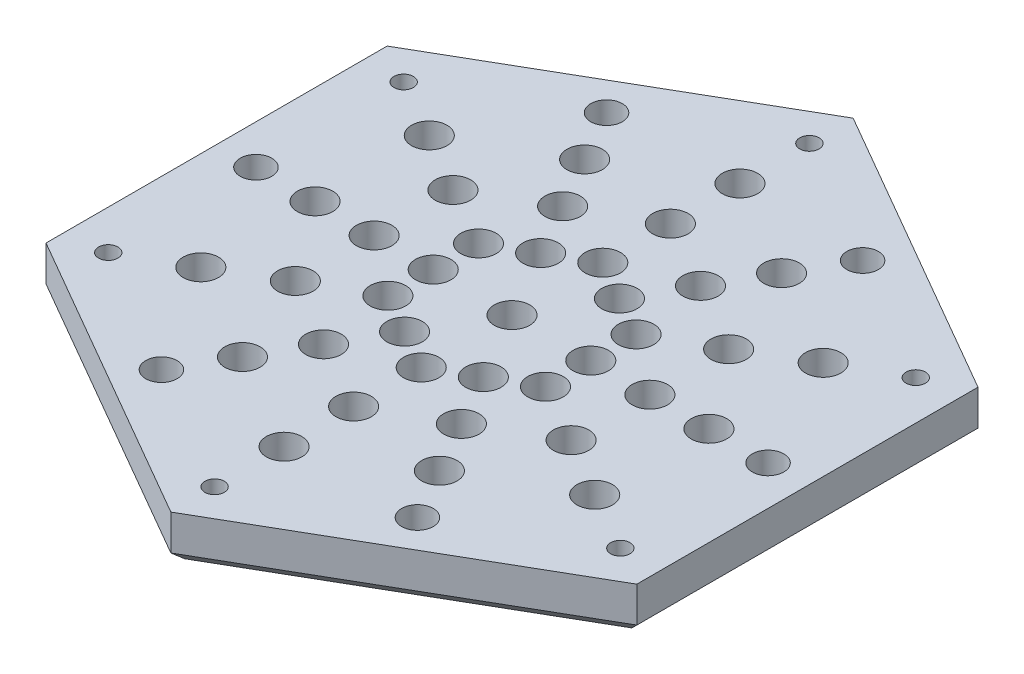
SolidWorks part; units mm, degrees
ref_plane "前基準面" through (0, 0, 0) normal (0, 0, 1) x (1, 0, 0)
ref_plane "上基準面" through (0, 0, 0) normal (0, 1, 0) x (1, 0, 0)
ref_plane "右基準面" through (0, 0, 0) normal (1, 0, 0) x (0, 0, -1)
ref_plane "平面1"
sketch "草圖1" plane through (0, 0, 0) normal (0, 1, 0) x (-1, 0, 0)
  line L0 (0, -86.6025) -> (-75, -43.3013)
  line L1 (-75, -43.3013) -> (-75, 43.3013)
  line L2 (-75, 43.3013) -> (0, 86.6025)
  line L3 (0, 86.6025) -> (75, 43.3013)
  line L4 (75, 43.3013) -> (75, -43.3013)
  line L5 (75, -43.3013) -> (0, -86.6025)
  dimension "D1" = 150
extrude "擠出1" add sketch "草圖1" along normal blind 12
chamfer "倒角1" distance 3 distance2 3 6 edges at (37.5, 0, 64.9519) (75, 0, 0) (-37.5, 0, 64.9519) (-75, 0, 0) (-37.5, 0, -64.9519) (37.5, 0, -64.9519)
sketch "草圖2" plane through (0, 12, 0) normal (0, 1, 0) x (-1, 0, 0)
  circle A0 centre (32.5, -56.5) radius 4
  circle A1 centre (-32.5, -56.5) radius 4
  circle A2 centre (65, 0) radius 4
  circle A3 centre (32.5, 56.5) radius 4
  circle A4 centre (-32.5, 56.5) radius 4
  circle A5 centre (-65, 0) radius 4
  dimension "D5" = 8
  dimension "D6" = 8
  dimension "D7" = 8
  dimension "D8" = 8
  dimension "D9" = 8
  dimension "D10" = 8
  dimension "D1" = 65
  dimension "D2" = 113
  dimension "D3" = 65
  dimension "D4" = 65
extrude "擠出2" cut sketch "草圖2" against normal blind 12 contours A4 | A3 | A5 | A1 | A0 | A2
hole_wizard "孔1" positions "草圖4" profile "草圖3" legacy
sketch "草圖4" plane through (0, 12, 0) normal (0, 1, 0) x (1, 0, 0)
  point P1 (0, 75.5)
  point P2 (-65, 37.5)
  point P3 (65, 37.5)
  point P4 (-65, -37.5)
  point P5 (65, -37.5)
  point P6 (0, -75.5)
sketch "草圖3" plane through (0, 12, -75.5) normal (1, 0, 0) x (0, 0, 1)
  line L0 (0, 0) -> (0, 18.5772)
  line L1 (0, 18.5772) -> (2.4585, 17.1)
  line L2 (2.4585, 17.1) -> (2.4585, 0)
  line L4 (2.4585, 0) -> (0, 0)
  line L6 (0, 18.5772) -> (-2.4585, 17.1) construction
  line L7 (0, -4.2442) -> (0, 117.3081) construction
  dimension "直徑" = 4.917
  dimension "深度" = 17.1
  dimension "導頭角度" = 118
cosmetic thread "裝飾螺紋線1" parameters "D1"=12, "D2"=6.294
cosmetic thread "裝飾螺紋線2" parameters "D1"=12, "D2"=6.294
cosmetic thread "裝飾螺紋線3" parameters "D1"=12, "D2"=6.294
cosmetic thread "裝飾螺紋線4" parameters "D1"=12, "D2"=6.294
cosmetic thread "裝飾螺紋線5" parameters "D1"=12, "D2"=6.294
cosmetic thread "裝飾螺紋線6" parameters "D1"=12, "D2"=6.294
sketch "草圖5" plane through (0, 12, 0) normal (0, 1, 0) x (-1, 0, 0)
  circle A0 centre (0, 0) radius 4.5
  dimension "D1" = 9
extrude "擠出4" cut sketch "草圖5" against normal blind 12
ref_plane "平面2" through (0, 12, 0) normal (0, 1, 0) x (1, 0, 0)
sketch "草圖6" plane through (0, 12, 0) normal (0, 1, 0) x (1, 0, 0)
  circle A0 centre (20, 0) radius 4.5
  circle A1 centre (35, 0) radius 4.5
  circle A2 centre (50, 0) radius 4.5
  dimension "D1" = 9
  dimension "D2" = 9
  dimension "D3" = 9
  dimension "D4" = 20
  dimension "D5" = 15
  dimension "D6" = 15
extrude "擠出3" cut sketch "草圖6" against normal blind 12 contours A0 | A1 | A2
ref_plane "平面3" through (0, 0, 0) normal (1, 0, 0) x (0, 1, 0)
mirror "鏡射5" about plane through (0, 0, 0) normal (1, 0, 0) of "擠出3"
ref_plane "平面4" through (0, 12, 0) normal (0, 1, 0) x (1, 0, 0)
sketch "草圖7" plane through (0, 12, 0) normal (0, 1, 0) x (1, 0, 0)
  circle A0 centre (20, 11.5) radius 4.5
  circle A1 centre (35, 20) radius 4.5
  circle A2 centre (50, 29) radius 4.5
  dimension "D1" = 9
  dimension "D2" = 9
  dimension "D3" = 9
extrude "擠出5" cut sketch "草圖7" against normal blind 12 contours A0 | A1 | A2
ref_plane "平面5" through (0, 0, 0) normal (0, 0, 1) x (1, 0, 0)
mirror "鏡射1" about plane through (0, 0, 0) normal (0, 0, 1) of "擠出5"
ref_plane "平面6" through (0, 0, 0) normal (1, 0, 0) x (0, 1, 0)
mirror "鏡射2" about plane through (0, 0, 0) normal (1, 0, 0) of "鏡射1", "擠出5"
ref_plane "平面7" through (0, 12, 0) normal (0, 1, 0) x (1, 0, 0)
sketch "草圖8" plane through (0, 12, 0) normal (0, 1, 0) x (1, 0, 0)
  circle A0 centre (0, -23.047) radius 4.5
  circle A1 centre (0, -40.2073) radius 4.5
  circle A2 centre (0, -57.8675) radius 4.5
  dimension "D1" = 9
  dimension "D2" = 9
  dimension "D3" = 9
extrude "擠出8" cut sketch "草圖8" against normal blind 12 contours A0 | A1 | A2
ref_plane "平面8" through (0, 0, 0) normal (0, 0, 1) x (1, 0, 0)
mirror "鏡射6" about plane through (0, 0, 0) normal (0, 0, 1) of "擠出8"
ref_plane "平面9" through (0, 12, 0) normal (0, 1, 0) x (1, 0, 0)
sketch "草圖9" plane through (0, 12, 0) normal (0, 1, 0) x (1, 0, 0)
  circle A0 centre (10, -17.2735) radius 4.5
  circle A1 centre (17.5, -30.3536) radius 4.5
  circle A2 centre (25, -43.4338) radius 4.5
  dimension "D1" = 9
  dimension "D2" = 9
  dimension "D3" = 9
extrude "擠出9" cut sketch "草圖9" against normal blind 12 contours A0 | A1 | A2
ref_plane "平面10" through (0, 0, 0) normal (1, 0, 0) x (0, 1, 0)
mirror "鏡射7" about plane through (0, 0, 0) normal (1, 0, 0) of "擠出9"
ref_plane "平面11" through (0, 0, 0) normal (0, 0, 1) x (1, 0, 0)
mirror "鏡射8" about plane through (0, 0, 0) normal (0, 0, 1) of "鏡射7", "擠出9"
